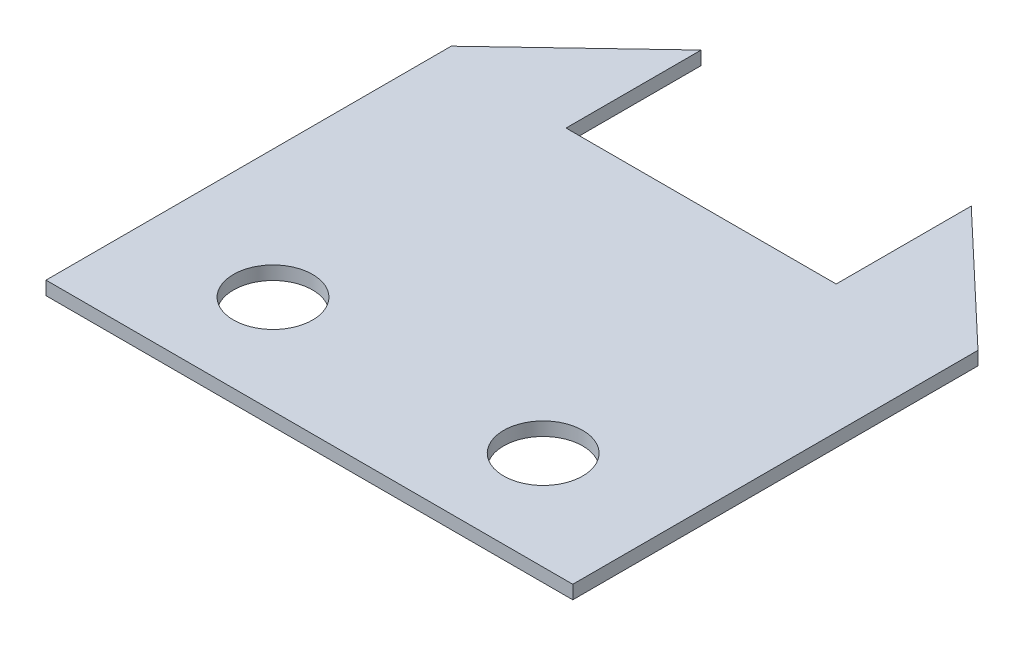
SolidWorks part; units mm, degrees
ref_plane "Plano frontal" through (0, 0, 0) normal (0, 0, 1) x (1, 0, 0)
ref_plane "Plano superior" through (0, 0, 0) normal (0, 1, 0) x (1, 0, 0)
ref_plane "Plano direito" through (0, 0, 0) normal (1, 0, 0) x (0, 0, -1)
sketch "Esboço1" plane through (0, 0, 0) normal (0, 1, 0) x (1, 0, 0)
  line L0 (-20, 48) -> (-39, 30)
  line L1 (-39, -30) -> (39, -30)
  line L2 (-39, -30) -> (-39, 30)
  line L4 (39, -30) -> (39, 30)
  line L5 (-39, -30) -> (39, 30) construction
  line L6 (-39, 30) -> (39, -30) construction
  line L11 (20, 48) -> (39, 30)
  line L12 (0, 55.5968) -> (0, 48) construction
  line L13 (0, 28) -> (0, -62.9596) construction
  line L15 (-20, 48) -> (-20, 28)
  line L16 (-20, 28) -> (20, 28)
  line L17 (20, 48) -> (20, 28)
  circle A0 centre (-20, -15.3846) radius 5.857
  circle A1 centre (20, -15.3846) radius 5.857
  point P0 (0, 0)
  dimension "D1" = 78
  dimension "D2" = 60
  dimension "D3" = 40
  dimension "D4" = 18
  dimension "D5" = 20
extrude "Ressalto-extrusão1" add sketch "Esboço1" along normal blind 2
